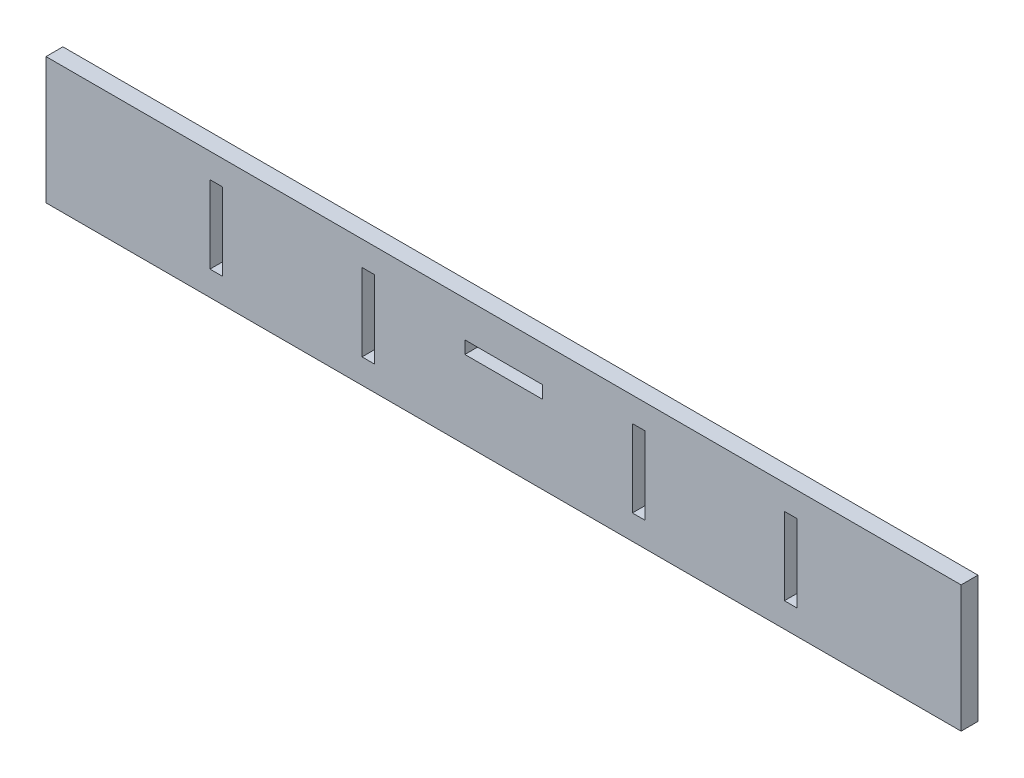
SolidWorks part; units mm, degrees
ref_plane "Front Plane" through (0, 0, 0) normal (0, 0, 1) x (1, 0, 0)
ref_plane "Top Plane" through (0, 0, 0) normal (0, 1, 0) x (1, 0, 0)
ref_plane "Right Plane" through (0, 0, 0) normal (1, 0, 0) x (0, 0, -1)
sketch "Sketch2" plane through (0, 0, 0) normal (0, 0, 1) x (1, 0, 0)
  line L1 (65, 9) -> (-65, 9)
  line L2 (65, 9) -> (65, -9)
  line L3 (65, -9) -> (-65, -9)
  line L4 (-65, 9) -> (-65, -9)
  line L5 (65, 9) -> (-65, -9) construction
  line L6 (65, -9) -> (-65, 9) construction
  point P0 (0, 0)
extrude "Boss-Extrude1" add sketch "Sketch2" along normal blind 2.4
sketch "Sketch3" plane through (0, 0, 2.4) normal (0, 0, 1) x (1, 0, 0)
  line L0 (0, 9) -> (0, -9)
  line L1 (65, 9) -> (-65, 9) construction
  line L2 (-65, -9) -> (65, -9) construction
  line L3 (0, 0) -> (-30, 0)
  line L4 (-30, 5.5) -> (-30, -5.5)
  line L5 (-20.1, -5.5) -> (-39.9, -5.5)
  line L6 (-20.1, -5.5) -> (-20.1, 5.5)
  line L7 (-20.1, 5.5) -> (-39.9, 5.5)
  line L8 (-39.9, -5.5) -> (-39.9, 5.5)
  line L9 (-20.1, -5.5) -> (-39.9, 5.5) construction
  line L10 (-20.1, 5.5) -> (-39.9, -5.5) construction
  line L11 (-39.9, 5.5) -> (-41.7, 5.5)
  line L12 (-39.9, 5.5) -> (-39.9, -5.5)
  line L13 (-39.9, -5.5) -> (-41.7, -5.5)
  line L14 (-41.7, 5.5) -> (-41.7, -5.5)
  line L15 (-20.1, -5.5) -> (-18.3, -5.5)
  line L16 (-20.1, -5.5) -> (-20.1, 5.5)
  line L17 (-20.1, 5.5) -> (-18.3, 5.5)
  line L18 (-18.3, 5.5) -> (-18.3, -5.5)
  line L19 (20.1, 5.5) -> (18.3, 5.5)
  line L20 (20.1, -5.5) -> (20.1, 5.5)
  line L21 (18.3, 5.5) -> (18.3, -5.5)
  line L22 (20.1, -5.5) -> (18.3, -5.5)
  line L23 (39.9, -5.5) -> (41.7, -5.5)
  line L24 (39.9, 5.5) -> (41.7, 5.5)
  line L25 (39.9, -5.5) -> (39.9, 5.5)
  line L26 (41.7, 5.5) -> (41.7, -5.5)
  line L27 (0, 9) -> (0, 3)
  line L28 (5.5, 3.9) -> (-5.5, 3.9)
  line L29 (5.5, 3.9) -> (5.5, 2.1)
  line L30 (5.5, 2.1) -> (-5.5, 2.1)
  line L31 (-5.5, 3.9) -> (-5.5, 2.1)
  line L32 (5.5, 3.9) -> (-5.5, 2.1) construction
  line L33 (5.5, 2.1) -> (-5.5, 3.9) construction
  point P27 (0, 3)
  point P33 (0, 0)
  point P34 (0, 0)
extrude "Cut-Extrude1" cut sketch "Sketch3" against normal blind 11 contours L11 L14 L13 L8 | L18 L17 L6 L3 | L18 L3 L6 L15 | L22 L20 L19 L21 | L26 L24 L25 L23 | L28 L31 L30 L0 L27 | L30 L29 L28 L27 L0
